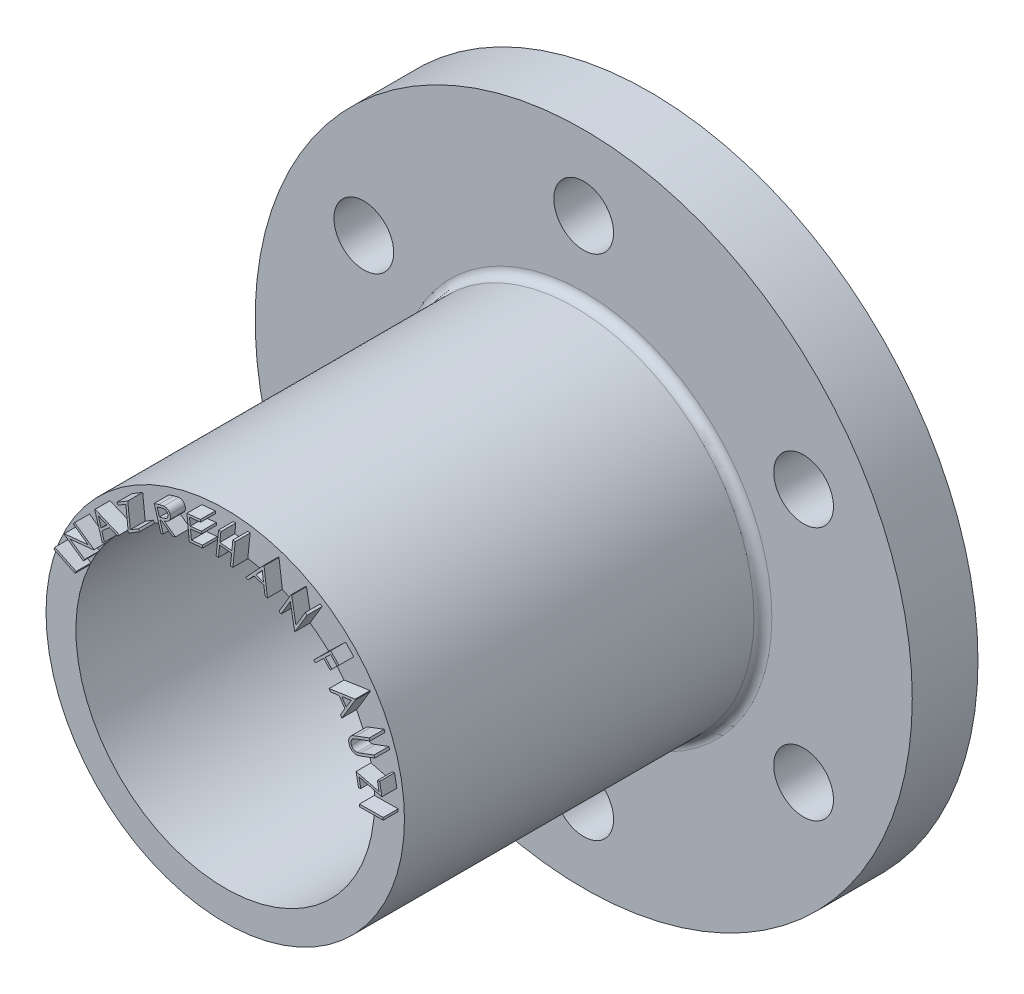
SolidWorks part; units mm, degrees
ref_plane "Front Plane" through (0, 0, 0) normal (0, 0, 1) x (1, 0, 0)
ref_plane "Top Plane" through (0, 0, 0) normal (0, 1, 0) x (1, 0, 0)
ref_plane "Right Plane" through (0, 0, 0) normal (1, 0, 0) x (0, 0, -1)
sketch "Sketch1" plane through (0, 0, 0) normal (0, 0, 1) x (1, 0, 0)
  circle A0 centre (0, 0) radius 110
  dimension "D1" = 220
extrude "Boss-Extrude1" add sketch "Sketch1" along normal blind 22
sketch "Sketch2" plane through (0, 0, 22) normal (0, 0, 1) x (1, 0, 0)
  circle A0 centre (0, 0) radius 60
  dimension "D1" = 120
extrude "Boss-Extrude2" add sketch "Sketch2" along normal blind 120
sketch "Sketch3" plane through (0, 0, 142) normal (0, 0, 1) x (1, 0, 0)
  circle A0 centre (0, 0) radius 50
  dimension "D1" = 100
extrude "Cut-Extrude1" cut sketch "Sketch3" against normal through all
sketch "Sketch4" plane through (0, 0, 22) normal (0, 0, 1) x (1, 0, 0)
  circle A0 centre (0, 85) radius 10
  circle A1 centre (73.6122, 42.5) radius 10
  circle A2 centre (73.6122, -42.5) radius 10
  circle A3 centre (0, -85) radius 10
  circle A4 centre (-73.6122, -42.5) radius 10
  circle A5 centre (-73.6122, 42.5) radius 10
  point P17 (0, 0)
  dimension "D1" = 20
  dimension "D2" = 85
  dimension "D3" = 6
extrude "Cut-Extrude2" cut sketch "Sketch4" against normal through all
fillet "Fillet1" radius 3 1 edges at (60, 0, 22)
sketch "Sketch5" plane through (0, 0, 142) normal (0, 0, 1) x (1, 0, 0)
  text T0 "I N A Z  R E H A N  F A U Z I" font "Century Gothic" height 8
extrude "Boss-Extrude3" add sketch "Sketch5" along normal blind 5
